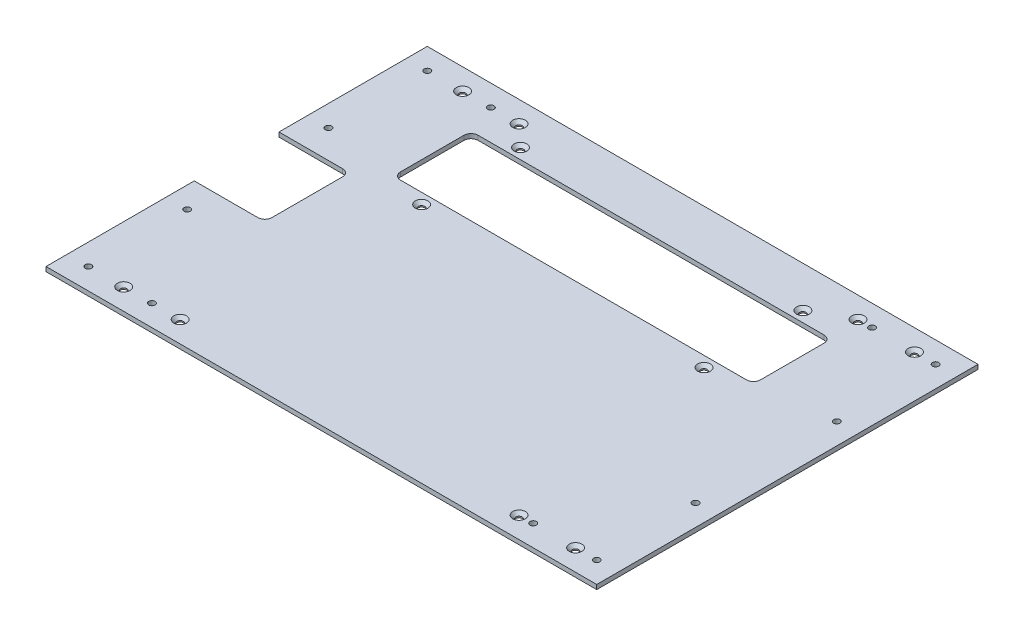
SolidWorks part; units mm, degrees
ref_plane "Front Plane" through (0, 0, 0) normal (0, 0, 1) x (1, 0, 0)
ref_plane "Top Plane" through (0, 0, 0) normal (0, 1, 0) x (1, 0, 0)
ref_plane "Right Plane" through (0, 0, 0) normal (1, 0, 0) x (0, 0, -1)
sketch "Sketch1" plane through (0, 0, 0) normal (0, 1, 0) x (1, 0, 0)
  line L1 (-195, -135) -> (195, -135)
  line L2 (-195, -135) -> (-195, 135)
  line L3 (-195, 135) -> (195, 135)
  line L4 (195, -135) -> (195, 135)
  line L5 (-195, -135) -> (195, 135) construction
  line L6 (-195, 135) -> (195, -135) construction
  point P0 (0, 0)
  dimension "D1" = 390
  dimension "D2" = 270
extrude "Boss-Extrude1" add sketch "Sketch1" along normal blind 3.175
hole_wizard "CSK for M4 SFHCS2" positions "Sketch4" profile "Sketch6" countersink size "M4" standard "ANSI Metric" end condition through all
sketch "Sketch4" plane through (0, 3.175, 0) normal (0, 1, 0) x (1, 0, 0)
  line L0 (-155, 120) -> (-115, 120)
  line L2 (125, 120) -> (165, 120)
  line L4 (195, 135) -> (-195, 135) construction
  point P1 (-155, 120)
  point P2 (-115, 120)
  point P5 (125, 120)
  point P6 (165, 120)
  point P11 (-135, 120)
  point P13 (145, 120)
  dimension "D1" = 40
  dimension "D2" = 40
  dimension "D3" = 15
  dimension "D4" = 60
  dimension "D5" = 50
sketch "Sketch6" plane through (-155, 3.175, -120) normal (1, 0, 0) x (0, 0, 1)
  line L0 (0, 0) -> (0, 3.175)
  line L1 (0, 3.175) -> (2.25, 3.175)
  line L2 (2.25, 3.175) -> (2.25, 2.23)
  line L3 (2.25, 2.23) -> (4.48, 0)
  line L5 (4.48, 0) -> (0, 0)
  line L6 (-2.25, 2.23) -> (-4.48, 0) construction
  line L11 (0, -6.35) -> (0, 107.95) construction
  dimension "Thru Hole Dia." = 4.5
  dimension "Thru Hole Depth" = 3.175
  dimension "Near C'Sink Dia." = 8.96
  dimension "Near C'Sink Angle" = 90
mirror "Mirror2" about plane through (0, 0, 0) normal (0, 0, 1) of "CSK for M4 SFHCS2"
hole_wizard "M4 Clearance Hole1" positions "Sketch7" profile "Sketch9" hole size "M4" standard "ANSI Metric" end condition through all
sketch "Sketch7" plane through (0, 3.175, 0) normal (0, 1, 0) x (1, 0, 0)
  line L0 (-195, 135) -> (-195, -135) construction
  line L1 (195, 135) -> (-195, 135) construction
  point P0 (-180, 120)
  point P2 (-180, 50)
  point P4 (-135, 120)
  dimension "D1" = 15
  dimension "D2" = 15
  dimension "D3" = 45
  dimension "D4" = 70
sketch "Sketch9" plane through (-180, 3.175, -120) normal (1, 0, 0) x (0, 0, 1)
  line L0 (0, 0) -> (0, 3.175)
  line L1 (0, 3.175) -> (2.25, 3.175)
  line L2 (2.25, 3.175) -> (2.25, 0)
  line L5 (2.25, 0) -> (0, 0)
  line L11 (0, -6.35) -> (0, 107.95) construction
  dimension "Thru Hole Dia." = 4.5
  dimension "Thru Hole Depth" = 3.175
mirror "Mirror3" about plane through (0, 0, 0) normal (1, 0, 0) of "M4 Clearance Hole1" second plane through (0, 0, 0) second plane normal (0, 0, 1)
sketch "Sketch10" plane through (0, 3.175, 0) normal (0, 1, 0) x (1, 0, 0)
  line L0 (195, 135) -> (-195, 135) construction
  line L1 (-127.5, 43.5) -> (127.5, 43.5)
  line L2 (-127.5, 43.5) -> (-127.5, 98.5)
  line L3 (-127.5, 98.5) -> (127.5, 98.5)
  line L4 (127.5, 43.5) -> (127.5, 98.5)
  line L5 (-127.5, 43.5) -> (127.5, 98.5) construction
  line L6 (-127.5, 98.5) -> (127.5, 43.5) construction
  point P0 (0, 71)
  dimension "D1" = 255
  dimension "D2" = 55
  dimension "D3" = 64
extrude "Cut-Extrude1" cut sketch "Sketch10" against normal blind 3.175
sketch "Sketch11" plane through (0, 3.175, 0) normal (0, 1, 0) x (1, 0, 0)
  line L0 (-195, 135) -> (-195, -135) construction
  line L1 (-145, -30) -> (-195, -30)
  line L2 (-145, -30) -> (-145, 30)
  line L3 (-145, 30) -> (-195, 30)
  line L4 (-195, -30) -> (-195, 30)
  line L5 (-145, -30) -> (-195, 30) construction
  line L6 (-145, 30) -> (-195, -30) construction
  point P0 (-170, 0)
  point P7 (-195, 0)
  dimension "D1" = 60
  dimension "D2" = 50
  dimension "D3" = 0
extrude "Cut-Extrude2" cut sketch "Sketch11" against normal blind 10
hole_wizard "CSK for M4 SFHCS3" positions "Sketch12" profile "Sketch13" countersink size "M4" standard "ANSI Metric" end condition through all
sketch "Sketch12" plane through (0, 3.175, 0) normal (0, 1, 0) x (1, 0, 0)
  line L1 (-100, 36) -> (100, 36)
  line L2 (-100, 36) -> (-100, 106)
  line L3 (-100, 106) -> (100, 106)
  line L4 (100, 36) -> (100, 106)
  line L5 (-100, 36) -> (100, 106) construction
  line L6 (-100, 106) -> (100, 36) construction
  line L7 (127.5, 98.5) -> (-127.5, 98.5) construction
  point P2 (100, 106)
  point P131 (-100, 36)
  point P132 (-100, 106)
  point P133 (100, 36)
  point P140 (0, 0)
  point P141 (0, 71)
  dimension "D1" = 200
  dimension "D2" = 70
  dimension "D3" = 7.5
sketch "Sketch13" plane through (100, 3.175, -106) normal (1, 0, 0) x (0, 0, 1)
  line L0 (0, 0) -> (0, 3.175)
  line L1 (0, 3.175) -> (2.25, 3.175)
  line L2 (2.25, 3.175) -> (2.25, 2.23)
  line L3 (2.25, 2.23) -> (4.48, 0)
  line L5 (4.48, 0) -> (0, 0)
  line L6 (-2.25, 2.23) -> (-4.48, 0) construction
  line L11 (0, -6.35) -> (0, 107.95) construction
  dimension "Thru Hole Dia." = 4.5
  dimension "Thru Hole Depth" = 3.175
  dimension "Near C'Sink Dia." = 8.96
  dimension "Near C'Sink Angle" = 90
fillet "Fillet1" radius 5 4 edges at (127.5, 1.5875, -43.5) (127.5, 1.5875, -98.5) (-127.5, 1.5875, -43.5) (-127.5, 1.5875, -98.5)
fillet "Fillet2" radius 5 2 edges at (-145, 1.5875, 30) (-145, 1.5875, -30)
